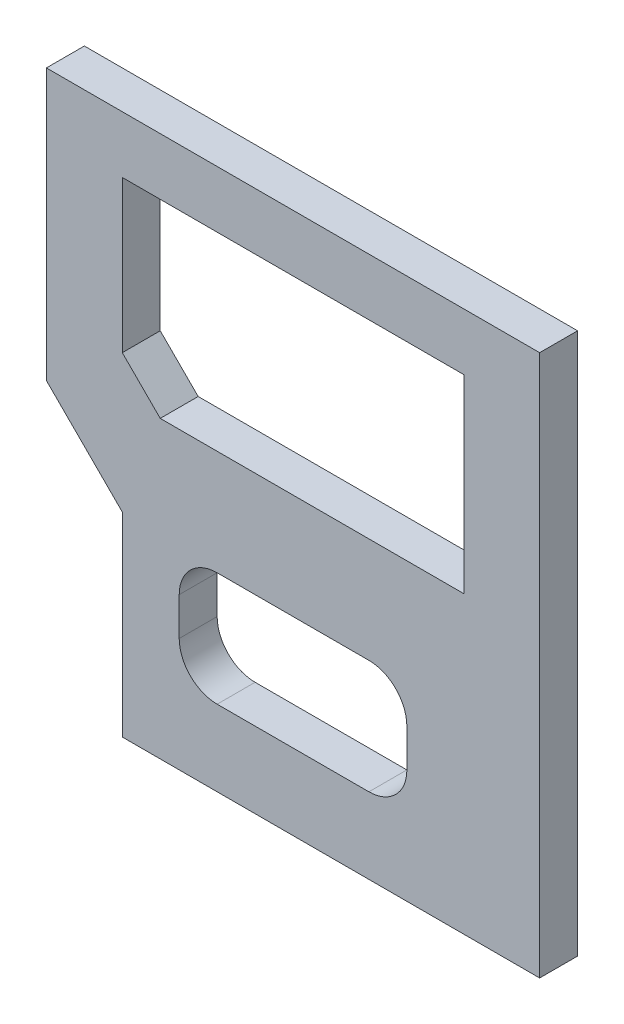
SolidWorks part; units mm, degrees
ref_plane "Front Plane" through (0, 0, 0) normal (0, 0, 1) x (1, 0, 0)
ref_plane "Top Plane" through (0, 0, 0) normal (0, 1, 0) x (1, 0, 0)
ref_plane "Right Plane" through (0, 0, 0) normal (1, 0, 0) x (0, 0, -1)
sketch "草图1" plane through (0, 0, 0) normal (0, 0, 1) x (1, 0, 0)
  line L17 (-65, 0) -> (-45, -20)
  line L22 (65, 71.367) -> (-65, 71.367)
  line L23 (65, 71.367) -> (65, -71.367)
  line L24 (65, -71.367) -> (-45, -71.367)
  line L25 (-65, 71.367) -> (-65, 0)
  line L26 (65, 71.367) -> (-65, -71.367) construction
  line L27 (65, -71.367) -> (-65, 71.367) construction
  line L28 (45, 56.367) -> (-45, 56.367)
  line L29 (45, 56.367) -> (45, 6.367)
  line L30 (45, 6.367) -> (-35, 6.367)
  line L31 (-45, 56.367) -> (-45, 16.367)
  line L32 (45, 56.367) -> (-45, 6.367) construction
  line L33 (45, 6.367) -> (-45, 56.367) construction
  line L34 (20, -21.367) -> (-20, -21.367)
  line L35 (30, -31.367) -> (30, -41.367)
  line L36 (20, -51.367) -> (-20, -51.367)
  line L37 (-30, -31.367) -> (-30, -41.367)
  line L38 (30, -21.367) -> (-30, -51.367) construction
  line L39 (30, -51.367) -> (-30, -21.367) construction
  line L40 (-45, -20) -> (-45, -71.367)
  line L43 (-65, -71.367) -> (-45, -71.367) construction
  line L44 (-45, 16.367) -> (-35, 6.367)
  arc A0 (-20, -51.367) -> (-30, -41.367) centre (-20, -41.367) cw
  arc A1 (-30, -31.367) -> (-20, -21.367) centre (-20, -31.367) cw
  arc A2 (30, -31.367) -> (20, -21.367) centre (20, -31.367) ccw
  arc A3 (30, -41.367) -> (20, -51.367) centre (20, -41.367) cw
  point P0 (0, 0)
  point P2 (0, 0)
  point P6 (0, 31.367)
  point P11 (0, -36.367)
  dimension "D12" = 10
  dimension "D8" = 60
  dimension "D9" = 35
  dimension "D10" = 30
  dimension "D11" = 20
extrude "凸台-拉伸1" add sketch "草图1" along normal blind 10
